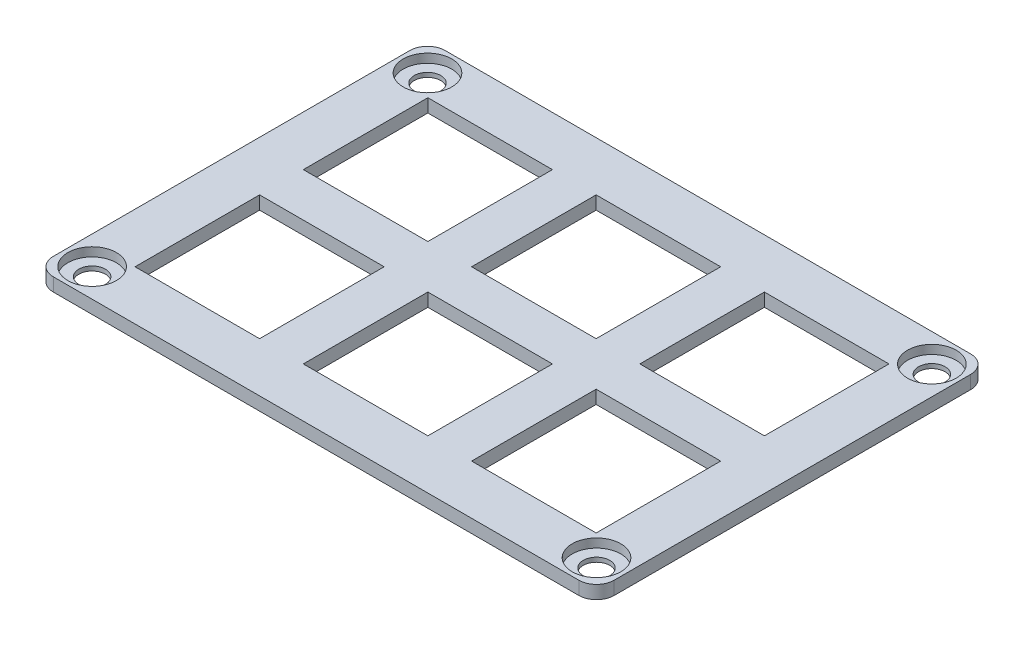
SolidWorks part; units mm, degrees
ref_plane "Front Plane" through (0, 0, 0) normal (0, 0, 1) x (1, 0, 0)
ref_plane "Top Plane" through (0, 0, 0) normal (0, 1, 0) x (1, 0, 0)
ref_plane "Right Plane" through (0, 0, 0) normal (1, 0, 0) x (0, 0, -1)
sketch "Sketch1" plane through (0, 0, 0) normal (0, 1, 0) x (1, 0, 0)
  line L1 (0, 0) -> (63.5, 0)
  line L2 (0, 0) -> (0, 44.3653)
  line L3 (0, 44.3653) -> (63.5, 44.3653)
  line L4 (63.5, 0) -> (63.5, 44.3653)
  dimension "D1" = 63.5
  dimension "D2" = 44.3653
extrude "Boss-Extrude1" add sketch "Sketch1" along normal blind 1.5
sketch "Sketch2" plane through (0, 1.5, 0) normal (0, 1, 0) x (1, 0, 0)
  line L0 (31.75, 44.3653) -> (31.75, 0) construction
  line L1 (5.65, 38.7577) -> (19.75, 38.7577)
  line L2 (5.65, 38.7577) -> (5.65, 24.6577)
  line L3 (5.65, 24.6577) -> (19.75, 24.6577)
  line L4 (19.75, 38.7577) -> (19.75, 24.6577)
  line L5 (24.7, 38.7577) -> (38.8, 38.7577)
  line L6 (24.7, 38.7577) -> (24.7, 24.6577)
  line L7 (24.7, 24.6577) -> (38.8, 24.6577)
  line L8 (38.8, 38.7577) -> (38.8, 24.6577)
  line L9 (43.75, 38.7577) -> (57.85, 38.7577)
  line L10 (43.75, 38.7577) -> (43.75, 24.6577)
  line L11 (43.75, 24.6577) -> (57.85, 24.6577)
  line L12 (57.85, 38.7577) -> (57.85, 24.6577)
  line L13 (5.65, 19.7077) -> (19.75, 19.7077)
  line L14 (5.65, 19.7077) -> (5.65, 5.6077)
  line L15 (5.65, 5.6077) -> (19.75, 5.6077)
  line L16 (19.75, 19.7077) -> (19.75, 5.6077)
  line L17 (24.7, 19.7077) -> (38.8, 19.7077)
  line L18 (24.7, 19.7077) -> (24.7, 5.6077)
  line L19 (24.7, 5.6077) -> (38.8, 5.6077)
  line L20 (38.8, 19.7077) -> (38.8, 5.6077)
  line L21 (43.75, 19.7077) -> (57.85, 19.7077)
  line L22 (43.75, 19.7077) -> (43.75, 5.6077)
  line L23 (43.75, 5.6077) -> (57.85, 5.6077)
  line L24 (57.85, 19.7077) -> (57.85, 5.6077)
  line L33 (63.5, 44.3653) -> (0, 44.3653) construction
  line L34 (0, 0) -> (63.5, 0) construction
  line L35 (0, 12.6577) -> (63.5, 12.6577) construction
  line L36 (0, 44.3653) -> (0, 0) construction
  line L37 (63.5, 0) -> (63.5, 44.3653) construction
  line L38 (12.7, 44.3653) -> (12.7, 0) construction
  line L39 (50.8, 44.3653) -> (50.8, 0) construction
  line L40 (0, 31.7077) -> (63.5, 31.7077) construction
  line L42 (22.225, 44.3653) -> (22.225, 0) construction
  circle A4 centre (3.2, 41.1653) radius 1.5
  circle A5 centre (60.3, 41.1653) radius 1.5
  circle A6 centre (60.3, 3.2) radius 1.5
  circle A7 centre (3.2, 3.2) radius 1.5
  point P52 (12.7, 24.6577)
  point P53 (19.75, 31.7077)
  point P54 (31.75, 24.6577)
  point P55 (38.8, 31.7077)
  point P56 (50.8, 24.6577)
  point P57 (57.85, 31.7077)
  point P58 (12.7, 5.6077)
  point P59 (19.75, 12.6577)
  point P60 (31.75, 5.6077)
  point P61 (38.8, 12.6577)
  point P62 (50.8, 5.6077)
  point P63 (57.85, 12.6577)
  dimension "D7" = 3
  dimension "D8" = 3.2
  dimension "D1" = 14.1
  dimension "D2" = 19.05
  dimension "D3" = 19.05
  dimension "D4" = 19.05
  dimension "D5" = 12.6577
  dimension "D6" = 9.525
  dimension "D9" = 3.2
  dimension "D10" = 3.2
  dimension "D11" = 3.2
  dimension "D12" = 3.2
  dimension "D13" = 3.2
  dimension "D14" = 3.2
  dimension "D15" = 3.2
extrude "Cut-Extrude1" cut sketch "Sketch2" against normal through all
sketch "Sketch4" plane through (0, 1.5, 0) normal (0, 1, 0) x (1, 0, 0)
  circle A5 centre (3.2, 41.1653) radius 2.75
  circle A6 centre (60.3, 41.1653) radius 2.75
  circle A7 centre (60.3, 3.2) radius 2.75
  circle A8 centre (3.2, 3.2) radius 2.75
  dimension "D1" = 5.5
  dimension "D2" = 5.5
  dimension "D3" = 5.5
  dimension "D4" = 5.5
extrude "Cut-Extrude2" cut sketch "Sketch4" against normal blind 1
fillet "Fillet1" radius 2 4 edges at (63.5, 0.75, -44.3653) (0, 0.75, -44.3653) (0, 0.75, 0) (63.5, 0.75, 0)
